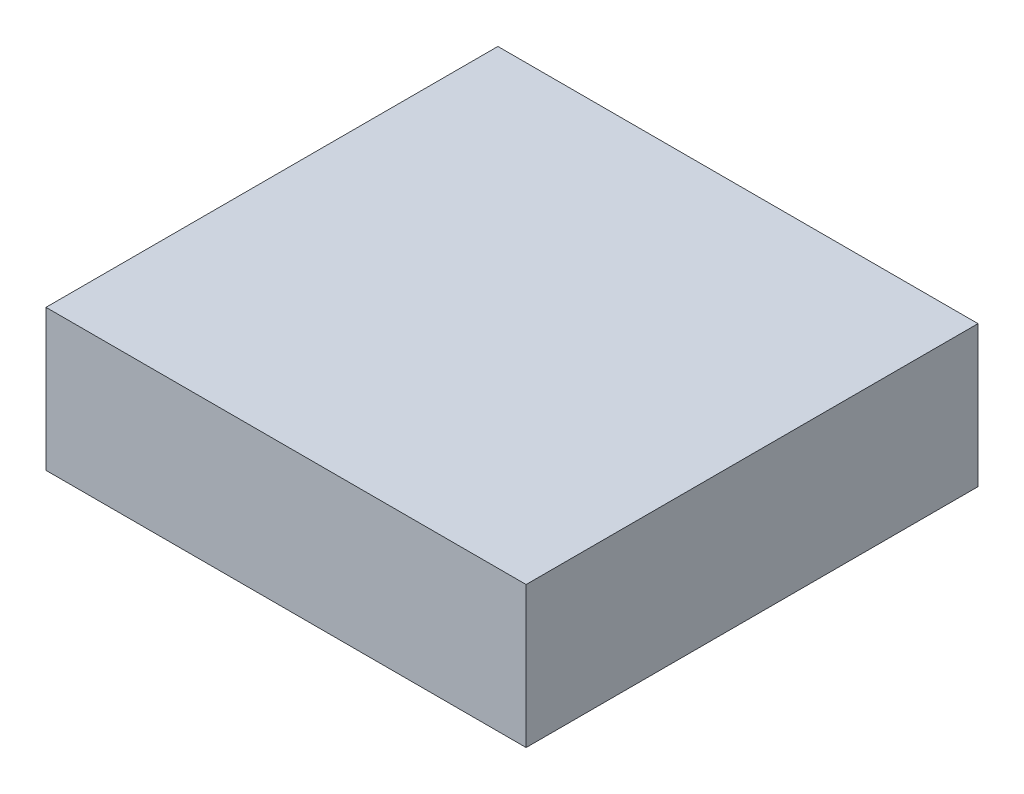
SolidWorks part; units mm, degrees
ref_plane "Front Plane" through (0, 0, 0) normal (0, 0, 1) x (1, 0, 0)
ref_plane "Top Plane" through (0, 0, 0) normal (0, 1, 0) x (1, 0, 0)
ref_plane "Right Plane" through (0, 0, 0) normal (1, 0, 0) x (0, 0, -1)
sketch "Sketch1" plane through (0, 0, 0) normal (0, 1, 0) x (1, 0, 0)
  line L1 (-8.5, 8) -> (8.5, 8)
  line L2 (-8.5, 8) -> (-8.5, -8)
  line L3 (-8.5, -8) -> (8.5, -8)
  line L4 (8.5, 8) -> (8.5, -8)
  line L5 (-8.5, 8) -> (8.5, -8) construction
  line L6 (-8.5, -8) -> (8.5, 8) construction
  point P1 (0, 0)
  dimension "D1" = 16
  dimension "D2" = 17
extrude "Boss-Extrude1" add sketch "Sketch1" along normal blind 5
